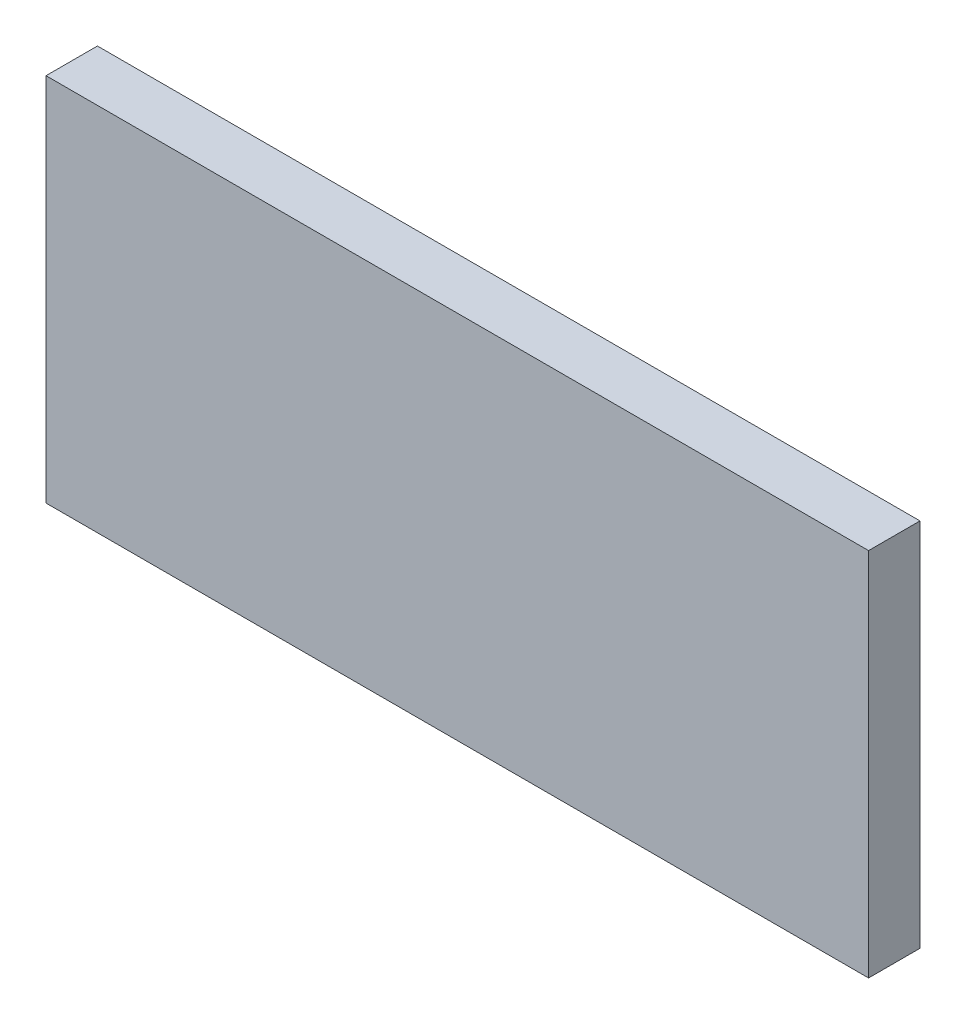
SolidWorks part; units mm, degrees
ref_plane "Front Plane" through (0, 0, 0) normal (0, 0, 1) x (1, 0, 0)
ref_plane "Top Plane" through (0, 0, 0) normal (0, 1, 0) x (1, 0, 0)
ref_plane "Right Plane" through (0, 0, 0) normal (1, 0, 0) x (0, 0, -1)
sketch "Sketch1" plane through (0, 0, 0) normal (0, 0, 1) x (1, 0, 0)
  line L0 (39.9302, 25.1698) -> (39.9302, 61.1698) construction
  line L1 (39.9302, 25.1698) -> (-40.0698, 25.1698) construction
  line L2 (-40.0698, 25.1698) -> (-40.0698, 61.1698) construction
  line L3 (39.9302, 61.1698) -> (-40.0698, 61.1698) construction
  line L4 (39.9302, 25.1698) -> (39.9302, 61.1698)
  line L5 (39.9302, 25.1698) -> (-40.0698, 25.1698)
  line L6 (-40.0698, 25.1698) -> (-40.0698, 61.1698)
  line L7 (39.9302, 61.1698) -> (-40.0698, 61.1698)
extrude "Boss-Extrude1" add sketch "Sketch1" along normal blind 5
sketch "Sketch2" plane through (0, 0, 0) normal (0, 0, -1) x (-1, 0, 0)
  line L4 (-35.5, 31.2) -> (35.5, 31.2)
  line L5 (-35.5, 55) -> (-35.5, 31.2)
  line L6 (35.5, 55) -> (-35.5, 55)
  line L7 (35.5, 31.2) -> (35.5, 55)
  line L8 (-35.5, 31.2) -> (35.5, 31.2)
  line L9 (-35.5, 55) -> (-35.5, 31.2)
  line L10 (35.5, 55) -> (-35.5, 55)
  line L11 (35.5, 31.2) -> (35.5, 55)
  dimension "D1" = 0
extrude "Boss-Extrude2" add sketch "Sketch2" along normal blind 2
